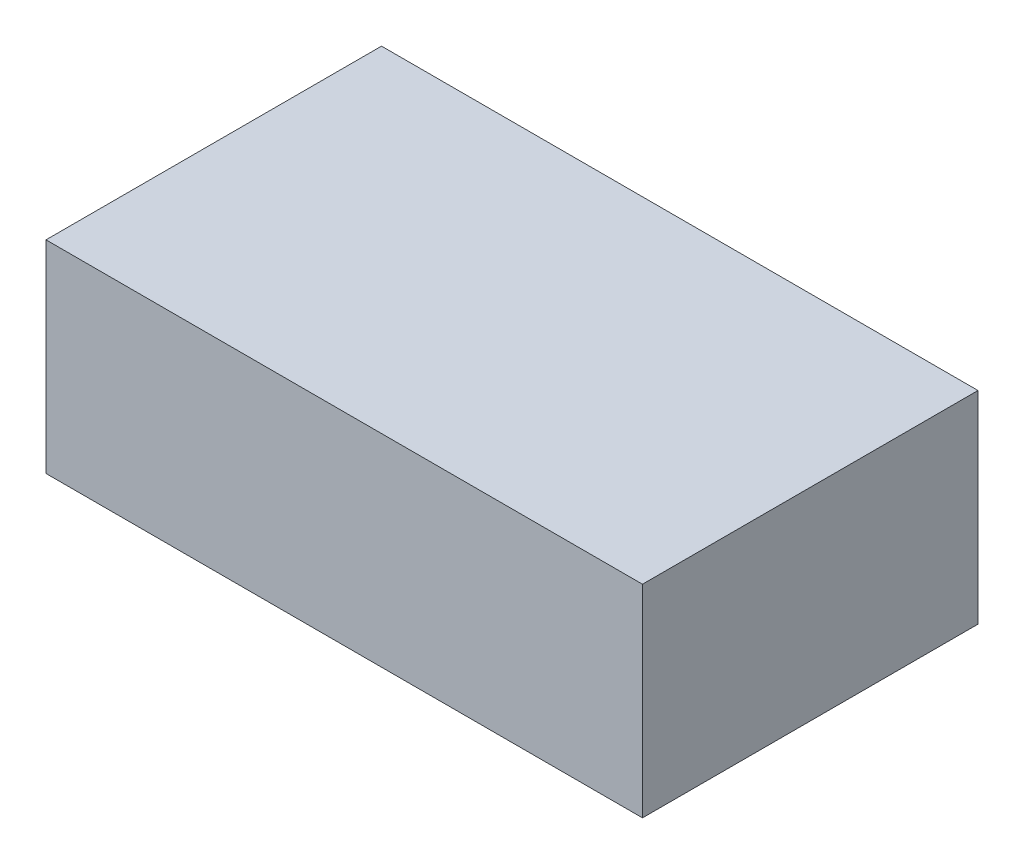
SolidWorks part; units mm, degrees
ref_plane "前视基准面" through (0, 0, 0) normal (0, 0, 1) x (1, 0, 0)
ref_plane "上视基准面" through (0, 0, 0) normal (0, 1, 0) x (1, 0, 0)
ref_plane "右视基准面" through (0, 0, 0) normal (1, 0, 0) x (0, 0, -1)
sketch "草图1" plane through (0, 0, 0) normal (0, 1, 0) x (1, 0, 0)
  line L1 (-56, 31.5) -> (56, 31.5)
  line L2 (-56, 31.5) -> (-56, -31.5)
  line L3 (-56, -31.5) -> (56, -31.5)
  line L4 (56, 31.5) -> (56, -31.5)
  line L5 (-56, 31.5) -> (56, -31.5) construction
  line L6 (-56, -31.5) -> (56, 31.5) construction
  point P0 (0, 0)
  dimension "D1" = 112
  dimension "D2" = 63
extrude "凸台-拉伸1" add sketch "草图1" along normal blind 38
